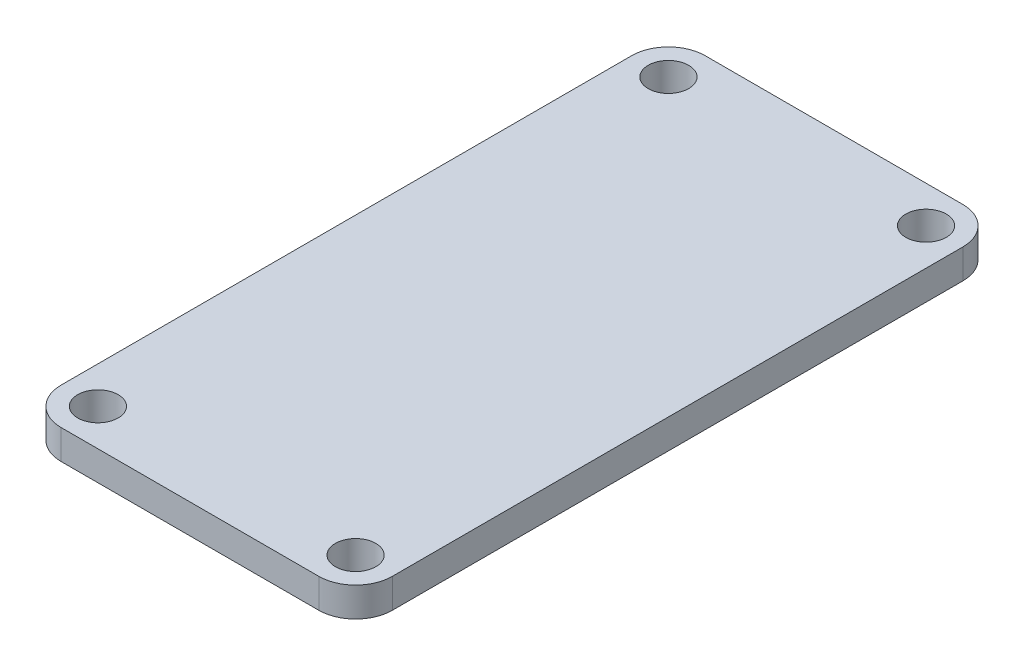
SolidWorks part; units mm, degrees
ref_plane "前视基准面" through (0, 0, 0) normal (0, 0, 1) x (1, 0, 0)
ref_plane "上视基准面" through (0, 0, 0) normal (0, 1, 0) x (1, 0, 0)
ref_plane "右视基准面" through (0, 0, 0) normal (1, 0, 0) x (0, 0, -1)
sketch "草图1" plane through (0, 0, 0) normal (0, 1, 0) x (1, 0, 0)
  line L1 (-9, 17.5) -> (9, 17.5)
  line L2 (-9, 17.5) -> (-9, -17.5)
  line L3 (-9, -17.5) -> (9, -17.5)
  line L4 (9, 17.5) -> (9, -17.5)
  line L5 (-9, 17.5) -> (9, -17.5) construction
  line L6 (-9, -17.5) -> (9, 17.5) construction
  point P0 (0, 0)
  dimension "D1" = 18
  dimension "D2" = 35
extrude "凸台-拉伸1" add sketch "草图1" along normal blind 1.6
sketch "草图2" plane through (0, 1.6, 0) normal (0, 1, 0) x (1, 0, 0)
  line L0 (0, 7.2243) -> (0, -3.7287) construction
  line L1 (2.7499, 0) -> (-2.7033, 0) construction
  line L2 (9, 17.5) -> (-9, 17.5) construction
  line L3 (-9, 17.5) -> (-9, -17.5) construction
  circle A0 centre (-7, 15.5) radius 1.1
  circle A1 centre (7, 15.5) radius 1.1
  circle A2 centre (7, -15.5) radius 1.1
  circle A3 centre (-7, -15.5) radius 1.1
  dimension "D1" = 2.2
  dimension "D2" = 2
  dimension "D3" = 2
extrude "切除-拉伸1" cut sketch "草图2" against normal through all
fillet "圆角2" radius 2 4 edges at (9, 0.8, -17.5) (9, 0.8, 17.5) (-9, 0.8, 17.5) (-9, 0.8, -17.5)
